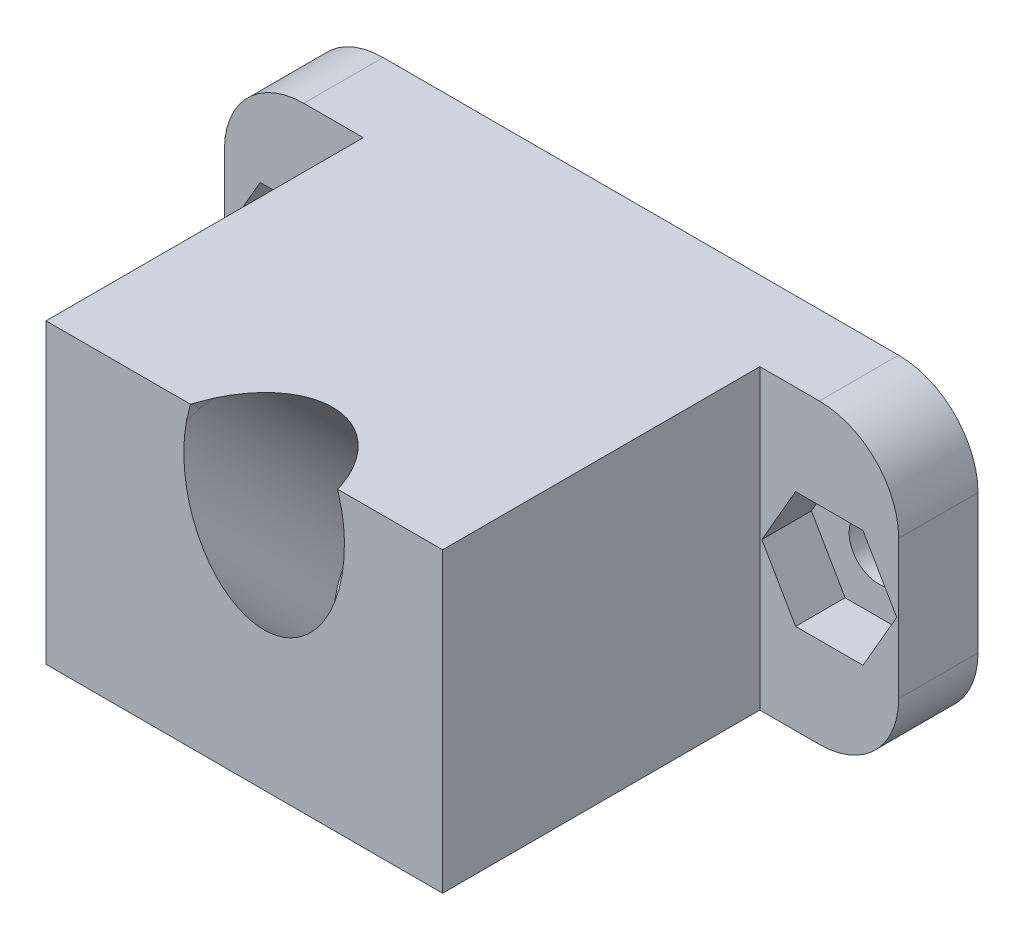
SolidWorks part; units mm, degrees
ref_plane "前视基准面" through (0, 0, 0) normal (0, 0, 1) x (1, 0, 0)
ref_plane "上视基准面" through (0, 0, 0) normal (0, 1, 0) x (1, 0, 0)
ref_plane "右视基准面" through (0, 0, 0) normal (1, 0, 0) x (0, 0, -1)
sketch "草图1" plane through (0, 0, 0) normal (0, 0, 1) x (1, 0, 0)
  line L1 (-10, 7.5) -> (10, 7.5)
  line L2 (-10, 7.5) -> (-10, -7.5)
  line L3 (-10, -7.5) -> (10, -7.5)
  line L4 (10, 7.5) -> (10, -7.5)
  line L5 (-10, 7.5) -> (10, -7.5) construction
  line L6 (-10, -7.5) -> (10, 7.5) construction
  point P0 (0, 0)
  dimension "D1" = 15
  dimension "D2" = 20
extrude "凸台-拉伸1" add sketch "草图1" along normal blind 20
sketch "草图2" plane through (0, 0, 0) normal (0, 0, 1) x (1, 0, 0)
  line L0 (-10, -7.5) -> (-17, -7.5)
  line L2 (10, 7.5) -> (-10, 7.5) construction
  line L3 (-10.1, 0) -> (-11.8, 2.9445)
  line L4 (-11.8, 2.9445) -> (-15.2, 2.9445)
  line L5 (-15.2, 2.9445) -> (-16.9, 0)
  line L6 (-16.9, 0) -> (-15.2, -2.9445)
  line L7 (-15.2, -2.9445) -> (-11.8, -2.9445)
  line L8 (-11.8, -2.9445) -> (-10.1, 0)
  line L9 (-10, 7.5) -> (-10, -7.5) construction
  line L10 (10, -7.5) -> (10, 7.5) construction
  line L11 (16.9, 0) -> (15.2, 2.9445)
  line L12 (15.2, 2.9445) -> (11.8, 2.9445)
  line L13 (11.8, 2.9445) -> (10.1, 0)
  line L14 (10.1, 0) -> (11.8, -2.9445)
  line L15 (11.8, -2.9445) -> (15.2, -2.9445)
  line L16 (15.2, -2.9445) -> (16.9, 0)
  line L18 (-10, 7.5) -> (-17, 7.5)
  line L19 (-10, 7.5) -> (-10, -7.5)
  line L21 (-17, 7.5) -> (-17, -7.5)
  line L22 (10, 7.5) -> (17, 7.5)
  line L23 (10, 7.5) -> (10, -7.5)
  line L24 (10, -7.5) -> (17, -7.5)
  line L25 (17, 7.5) -> (17, -7.5)
  circle A2 centre (-13.5, 0) radius 2.9445 construction
  circle A3 centre (13.5, 0) radius 2.9445 construction
  dimension "D3" = 3.5
  dimension "D4" = 3.4
  dimension "D1" = 3.4
  dimension "D2" = 7.5
  dimension "D5" = 7.5
  dimension "D6" = 3.5
  dimension "D7" = 7
  dimension "D8" = 7
extrude "凸台-拉伸6" add sketch "草图2" along normal blind 4
ref_plane "基准面1" through (0, 6.25, 6.25) normal (0, 0.7071, 0.7071) x (1, 0, 0)
sketch "草图9" plane through (0, 0, 0) normal (0, 0, -1) x (-1, 0, 0)
  line L1 (-10.1, 0) -> (-11.8, 2.9445)
  line L2 (-11.8, 2.9445) -> (-15.2, 2.9445)
  line L3 (-15.2, 2.9445) -> (-16.9, 0)
  line L4 (-16.9, 0) -> (-15.2, -2.9445)
  line L5 (-15.2, -2.9445) -> (-11.8, -2.9445)
  line L6 (-11.8, -2.9445) -> (-10.1, 0)
  line L7 (16.9, 0) -> (15.2, 2.9445)
  line L8 (15.2, 2.9445) -> (11.8, 2.9445)
  line L9 (11.8, 2.9445) -> (10.1, 0)
  line L10 (10.1, 0) -> (11.8, -2.9445)
  line L11 (11.8, -2.9445) -> (15.2, -2.9445)
  line L12 (15.2, -2.9445) -> (16.9, 0)
  circle A0 centre (-13.5, 0) radius 2.9445 construction
  circle A1 centre (13.5, 0) radius 2.9445 construction
extrude "凸台-拉伸7" add sketch "草图9" against normal blind 1.5
sketch "草图10" plane through (0, 0, 0) normal (0, 0, -1) x (-1, 0, 0)
  circle A0 centre (-13.5, 0) radius 1.5
  circle A1 centre (13.5, 0) radius 1.5
extrude "切除-拉伸4" cut sketch "草图10" against normal blind 1.5
fillet "圆角1" radius 4 4 edges at (17, 7.5, 2) (17, -7.5, 2) (-17, 7.5, 2) (-17, -7.5, 2)
ref_plane "基准面2" through (0, 13.3211, 13.3211) normal (0, 0.7071, 0.7071) x (1, 0, 0)
sketch "草图11" plane through (0, 13.3211, 13.3211) normal (0, 0.7071, 0.7071) x (1, 0, 0)
  circle A0 centre (1, -10.4454) radius 4.05
extrude "切除-拉伸5" cut sketch "草图11" against normal blind 13
sketch "草图12" plane through (0, 13.3211, 13.3211) normal (0, -0.7071, -0.7071) x (1, 0, 0)
  line L0 (4.3918, 8.2322) -> (-2.3918, 8.2322)
  line L1 (-2.3918, 8.2322) -> (-2.7081, 8.8169)
  line L2 (-2.7081, 8.8169) -> (-2.9246, 9.4454)
  line L3 (-2.9246, 9.4454) -> (4.9246, 9.4454)
  line L4 (4.9246, 9.4454) -> (4.6437, 8.6773)
  line L5 (4.6437, 8.6773) -> (4.3918, 8.2322)
  arc A0 (-2.9246, 9.4454) -> (-2.3918, 8.2322) centre (1, 10.4454) ccw construction
  arc A1 (4.3918, 8.2322) -> (4.9246, 9.4454) centre (1, 10.4454) ccw construction
extrude "切除-拉伸6" cut sketch "草图12" against normal blind 10
